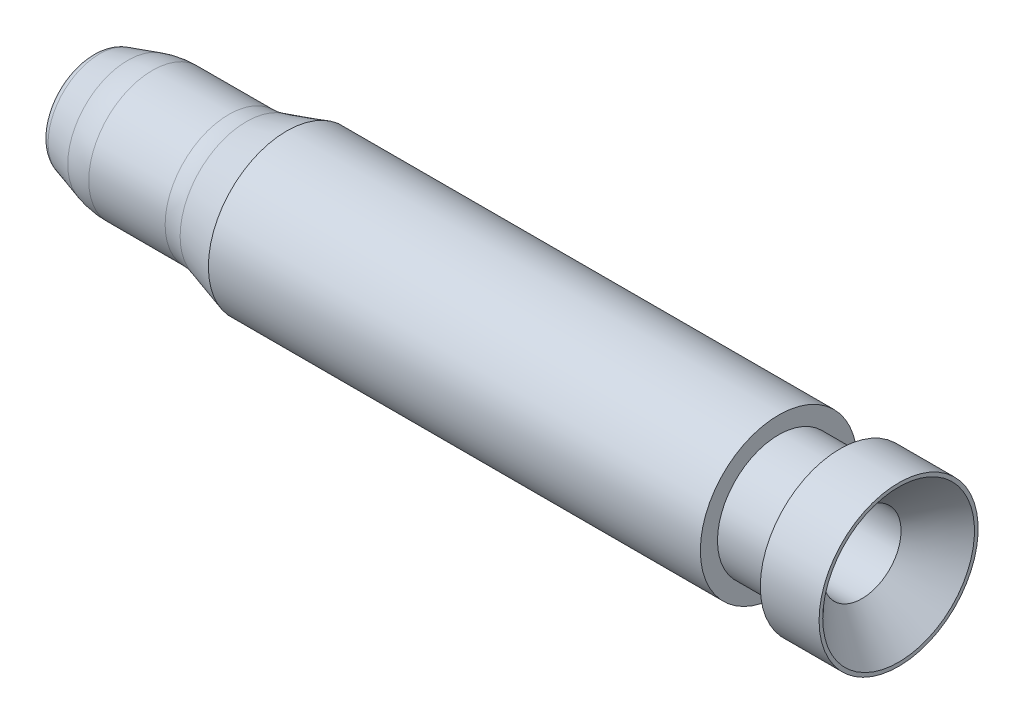
SolidWorks part; units mm, degrees
material "AISI 1020"
ref_plane "Plano superior" through (0, 0, 0) normal (0, 0, 1) x (1, 0, 0)
ref_plane "Plano frontal" through (0, 0, 0) normal (0, 1, 0) x (1, 0, 0)
ref_plane "Plano direito" through (0, 0, 0) normal (1, 0, 0) x (0, 0, -1)
sketch "Esboço1" plane through (0, 0, 0) normal (0, 1, 0) x (1, 0, 0)
  line L0 (0, 0) -> (101.5863, 0) construction
  line L1 (0.0008, 3.2) -> (66, 3.2)
  line L2 (66, 3.2) -> (66, 6.5)
  line L3 (66, 6.5) -> (61.2, 6.5)
  line L4 (61.2, 6.5) -> (61.2, 5)
  line L5 (61.2, 5) -> (56.2, 5)
  line L6 (56.2, 5) -> (56.2, 6.4)
  line L7 (56.2, 6.4) -> (16.0008, 6.4)
  line L8 (16.0008, 6.4) -> (12.0008, 5.2)
  line L9 (12.0008, 5.2) -> (4.0008, 5.2)
  line L10 (4.0008, 5.2) -> (0.0008, 4)
  line L12 (0.0008, 3.2) -> (0.0008, 4)
  point P11 (0.0008, 3.6)
  dimension "D1" = 66
  dimension "D2" = 3.2
  dimension "D3" = 5
  dimension "D4" = 6.4
  dimension "D5" = 1.4
  dimension "D6" = 4.8
  dimension "D7" = 5.2
  dimension "D8" = 16
  dimension "D9" = 4
  dimension "D10" = 8
  dimension "D11" = 4
revolve "Revolução1" add sketch "Esboço1" angle 360 about L0
fillet "Filete2" radius 7 1 edges at (4.0008, 0, 5.2)
fillet "Filete3" radius 5 1 edges at (12.0008, 0, 5.2)
chamfer "Chanfro1" distance 3 angle 45 1 edges at (66, 0, 3.2)
fillet "Filete6" radius 1 1 edges at (0.0008, 0, 4)
